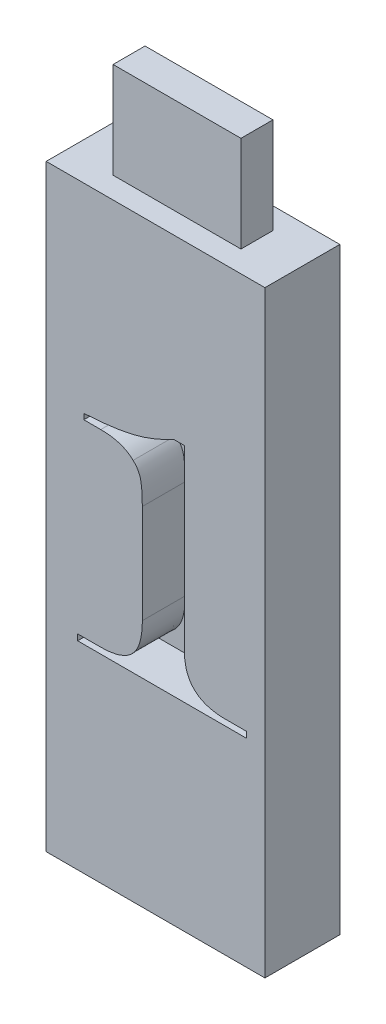
SolidWorks part; units mm, degrees
ref_plane "Front Plane" through (0, 0, 0) normal (0, 0, 1) x (1, 0, 0)
ref_plane "Top Plane" through (0, 0, 0) normal (0, 1, 0) x (1, 0, 0)
ref_plane "Right Plane" through (0, 0, 0) normal (1, 0, 0) x (0, 0, -1)
sketch "Sketch1" plane through (0, 0, 0) normal (0, 0, 1) x (1, 0, 0)
  line L1 (-8.69, -23.749) -> (8.69, -23.749)
  line L2 (-8.69, -23.749) -> (-8.69, 23.749)
  line L3 (-8.69, 23.749) -> (8.69, 23.749)
  line L4 (8.69, -23.749) -> (8.69, 23.749)
  line L5 (-8.69, -23.749) -> (8.69, 23.749) construction
  line L6 (-8.69, 23.749) -> (8.69, -23.749) construction
  point P0 (0, 0)
  dimension "D1" = 17.38
  dimension "D2" = 47.498
extrude "Boss-Extrude1" add sketch "Sketch1" along normal blind 5.95
sketch "Sketch2" plane through (0, 0, 5.95) normal (0, 0, 1) x (1, 0, 0)
  line L0 (0, 23.749) -> (0, -23.749) construction
  line L1 (8.69, 23.749) -> (-8.69, 23.749) construction
  line L2 (-8.69, -23.749) -> (8.69, -23.749) construction
  line L3 (0, -23.749) -> (0, 0) construction
  line L4 (0, 0) -> (-8.69, 0) construction
  line L5 (-8.69, 23.749) -> (-8.69, -23.749) construction
  line L6 (-8.69, 0) -> (8.69, 0) construction
  line L7 (8.69, -23.749) -> (8.69, 23.749) construction
  line L8 (-8.69, -23.749) -> (8.69, -23.749) construction
  line L9 (-8.69, -21.209) -> (8.69, -21.209) construction
  line L10 (-8.69, -18.669) -> (8.69, -18.669) construction
  line L11 (-8.69, -16.129) -> (8.69, -16.129) construction
  line L12 (-8.69, -13.589) -> (8.69, -13.589) construction
  line L13 (-8.69, -11.049) -> (8.69, -11.049) construction
  line L14 (-8.69, -8.509) -> (8.69, -8.509) construction
  line L15 (-8.69, -5.969) -> (8.69, -5.969) construction
  line L16 (-8.69, -3.429) -> (8.69, -3.429) construction
  line L17 (-8.69, -0.889) -> (8.69, -0.889) construction
  line L18 (-8.69, 1.651) -> (8.69, 1.651) construction
  line L19 (-8.69, 4.191) -> (8.69, 4.191) construction
  line L20 (-8.69, 6.731) -> (8.69, 6.731) construction
  line L21 (-8.69, 9.271) -> (8.69, 9.271) construction
  line L22 (-8.69, 11.811) -> (8.69, 11.811) construction
  line L23 (-8.69, 14.351) -> (8.69, 14.351) construction
  line L24 (-8.69, 16.891) -> (8.69, 16.891) construction
  line L25 (-8.69, 19.431) -> (8.69, 19.431) construction
  line L26 (-8.69, 21.971) -> (8.69, 21.971) construction
  line L27 (-8.69, 23.749) -> (-8.69, -23.749) construction
  line L28 (-6.15, 23.749) -> (-6.15, -23.749) construction
  line L29 (-3.61, 23.749) -> (-3.61, -23.749) construction
  line L30 (-1.07, 23.749) -> (-1.07, -23.749) construction
  line L31 (1.47, 23.749) -> (1.47, -23.749) construction
  line L32 (4.01, 23.749) -> (4.01, -23.749) construction
  line L33 (6.55, 23.749) -> (6.55, -23.749) construction
  text T0 "1\r\n" font "Engravers MT" height in points 72
  point P14 (0, 0)
  point P69 (-7.968, -5.969)
  point P70 (-8.2943, -5.969)
  point P71 (-8.0437, -5.969)
  point P72 (-7.9766, -7.9877)
  dimension "D1" = 19
  dimension "D2" = 2.54
  dimension "D4" = 2.54
  dimension "D3" = 7
extrude "Cut-Extrude1" cut sketch "Sketch2" against normal blind 3.41
sketch "Sketch3" plane through (0, 23.749, 0) normal (0, 1, 0) x (1, 0, 0)
  line L0 (0, 0) -> (0, -5.95) construction
  line L1 (8.69, -5.95) -> (-8.69, -5.95) construction
  line L2 (0, -5.95) -> (0, -2.975) construction
  line L3 (0, -2.975) -> (-8.69, -2.975) construction
  line L4 (-8.69, -5.95) -> (-8.69, 0) construction
  line L5 (-8.69, -2.975) -> (8.69, -2.975) construction
  line L6 (8.69, -5.95) -> (8.69, 0) construction
  line L8 (-5.08, -4.245) -> (5.08, -4.245)
  line L9 (-5.08, -4.245) -> (-5.08, -1.705)
  line L10 (-5.08, -1.705) -> (5.08, -1.705)
  line L11 (5.08, -4.245) -> (5.08, -1.705)
  line L12 (-5.08, -4.245) -> (5.08, -1.705) construction
  line L13 (-5.08, -1.705) -> (5.08, -4.245) construction
  dimension "D1" = 2.54
  dimension "D2" = 10.16
extrude "Boss-Extrude2" add sketch "Sketch3" along normal blind 7.62
